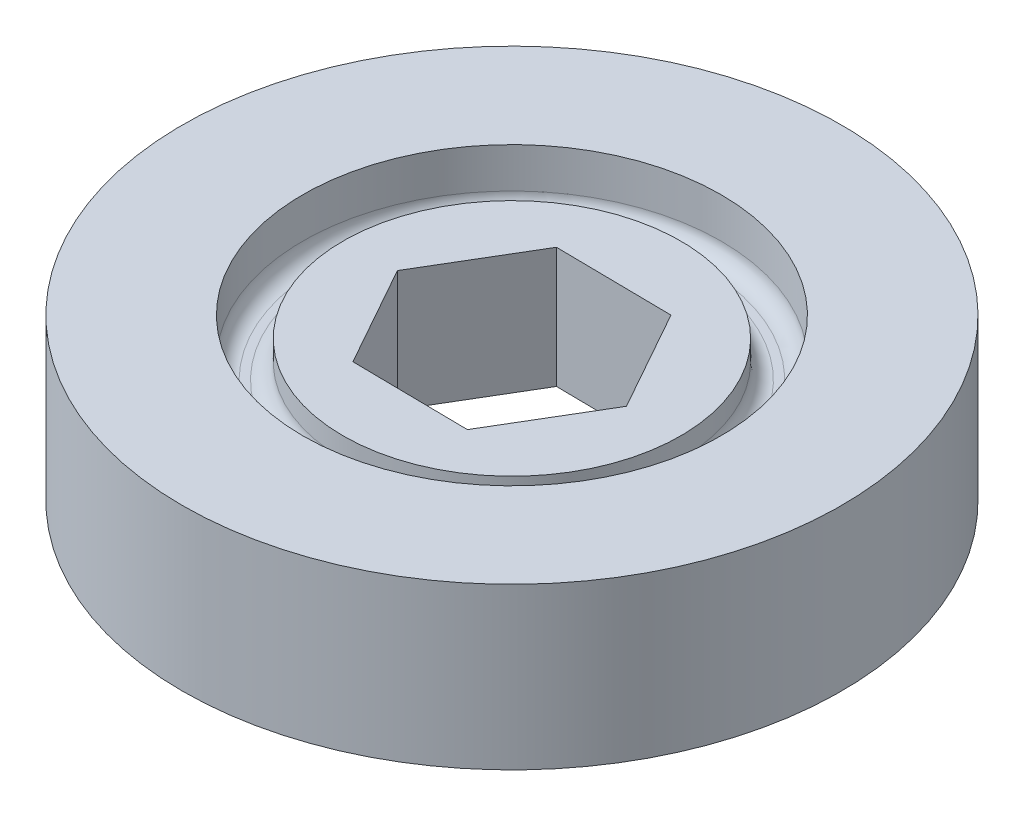
SolidWorks part; units mm, degrees
ref_plane "Front Plane" through (0, 0, 0) normal (0, 0, 1) x (1, 0, 0)
ref_plane "Top Plane" through (0, 0, 0) normal (0, 1, 0) x (1, 0, 0)
ref_plane "Right Plane" through (0, 0, 0) normal (1, 0, 0) x (0, 0, -1)
sketch "Sketch1" plane through (0, 0, 0) normal (0, 1, 0) x (1, 0, 0)
  circle A0 centre (0, 0) radius 20.5
  dimension "D1" = 41
extrude "Boss-Extrude1" add sketch "Sketch1" along normal blind 10
sketch "Sketch2" plane through (0, 10, 0) normal (0, 1, 0) x (1, 0, 0)
  circle A0 centre (0, 0) radius 13
  circle A1 centre (0, 0) radius 20.5 construction
  dimension "D1" = 7.5
extrude "Cut-Extrude1" cut sketch "Sketch2" against normal blind 3.5
sketch "Sketch3" plane through (0, 0, 0) normal (0, -1, 0) x (1, 0, 0)
  circle A0 centre (0, 0) radius 13
  circle A1 centre (0, 0) radius 20.5 construction
  dimension "D1" = 7.5
extrude "Cut-Extrude2" cut sketch "Sketch3" against normal blind 3.5
sketch "Sketch5" plane through (0, 6.5, 0) normal (0, 1, 0) x (1, 0, 0)
  circle A0 centre (0, 0) radius 10.5
  dimension "D1" = 21
extrude "Boss-Extrude2" add sketch "Sketch5" along normal blind 2.25
sketch "Sketch6" plane through (0, 3.5, 0) normal (0, -1, 0) x (1, 0, 0)
  circle A0 centre (0, 0) radius 10.5
  dimension "D1" = 21
extrude "Boss-Extrude3" add sketch "Sketch6" along normal blind 2.25
sketch "Sketch4" plane through (0, 6.5, 0) normal (0, 1, 0) x (1, 0, 0)
  line L1 (3.6896, 6.2024) -> (-3.5266, 6.2965)
  line L2 (-3.5266, 6.2965) -> (-7.2163, 0.0941)
  line L3 (-7.2163, 0.0941) -> (-3.6896, -6.2024)
  line L4 (-3.6896, -6.2024) -> (3.5266, -6.2965)
  line L5 (3.5266, -6.2965) -> (7.2163, -0.0941)
  line L6 (7.2163, -0.0941) -> (3.6896, 6.2024)
  circle A0 centre (0, 0) radius 6.25 construction
  dimension "D1" = 12.5
extrude "Cut-Extrude3" cut sketch "Sketch4" against normal through all both and the other way through all
fillet "Fillet1" radius 1 2 edges at (0, 3.5, -13) (0, 6.5, 13)
fillet "Fillet2" radius 1 2 edges at (0, 3.5, -10.5) (0, 6.5, 10.5)
